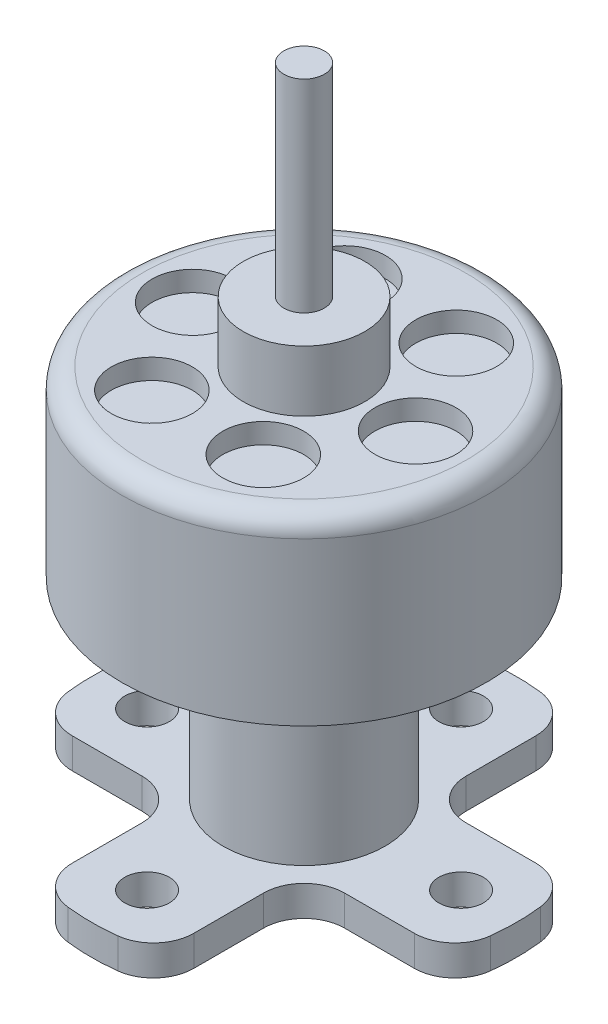
SolidWorks part; units mm, degrees
material "Liga 1060"
ref_plane "Plano frontal" through (0, 0, 0) normal (0, 0, 1) x (1, 0, 0)
ref_plane "Plano superior" through (0, 0, 0) normal (0, 1, 0) x (1, 0, 0)
ref_plane "Plano direito" through (0, 0, 0) normal (1, 0, 0) x (0, 0, -1)
sketch "Esboço1" plane through (0, 0, 0) normal (0, 1, 0) x (1, 0, 0)
  line L0 (-3, 3) -> (-3, 10.0623)
  line L1 (-10.0623, 3) -> (-3, 3)
  line L2 (3, 3) -> (3, 10.0623)
  line L3 (-10.0623, -3) -> (-3, -3)
  line L4 (3, -3) -> (10.0623, -3)
  line L5 (3, 3) -> (10.0623, 3)
  line L8 (3, -10.0623) -> (3, -3)
  line L10 (-3, -10.0623) -> (-3, -3)
  arc A0 (10.0623, -3) -> (10.0623, 3) centre (0, 0) ccw
  arc A1 (-3, -10.0623) -> (3, -10.0623) centre (0, 0) ccw
  arc A2 (-10.0623, 3) -> (-10.0623, -3) centre (0, 0) ccw
  arc A3 (3, 10.0623) -> (-3, 10.0623) centre (0, 0) ccw
  point P0 (0, 0)
  point P6 (0, 0)
  dimension "D2" = 10.5
  dimension "D1" = 6
extrude "Ressalto-extrusão1" add sketch "Esboço1" along normal blind 1.5
sketch "Esboço2" plane through (0, 1.5, 0) normal (0, 1, 0) x (1, 0, 0)
  line L0 (3, 3) -> (3, 10.0623) construction
  circle A0 centre (-7.75, 0) radius 1.1
  circle A1 centre (0, 7.75) radius 1.1
  circle A2 centre (7.75, 0) radius 1.1
  circle A3 centre (0, -7.75) radius 1.1
  point P12 (0, 0)
  dimension "D1" = 2.2
  dimension "D2" = 7.75
  dimension "D4" = 4.75
  dimension "D5" = 3
  dimension "D3" = 4
extrude "Corte-extrusão1" cut sketch "Esboço2" against normal up to next
fillet "Filete1" radius 2 12 edges at (10.0623, 0.75, 3) (3, 0.75, 3) (3, 0.75, 10.0623) (-3, 0.75, 10.0623) (-3, 0.75, 3) (-10.0623, 0.75, 3) (-10.0623, 0.75, -3) (-3, 0.75, -3) (-3, 0.75, -10.0623) (3, 0.75, -10.0623) (10.0623, 0.75, -3) (3, 0.75, -3)
sketch "Esboço3" plane through (0, 1.5, 0) normal (0, 1, 0) x (1, 0, 0)
  circle A0 centre (0, 0) radius 4
  dimension "D1" = 8
extrude "Ressalto-extrusão2" add sketch "Esboço3" along normal blind 9.5
sketch "Esboço4" plane through (0, 11, 0) normal (0, 1, 0) x (1, 0, 0)
  circle A0 centre (0, 0) radius 9
  dimension "D1" = 18
extrude "Ressalto-extrusão3" add sketch "Esboço4" along normal blind 9
fillet "Filete2" radius 1 1 edges at (0, 20, 9)
sketch "Esboço5" plane through (0, 20, 0) normal (0, 1, 0) x (1, 0, 0)
  circle A0 centre (0, 0) radius 3
  dimension "D1" = 6
extrude "Ressalto-extrusão4" add sketch "Esboço5" along normal blind 3
sketch "Esboço6" plane through (0, 23, 0) normal (0, 1, 0) x (1, 0, 0)
  circle A0 centre (0, 0) radius 1
  dimension "D1" = 2
extrude "Ressalto-extrusão5" add sketch "Esboço6" along normal blind 10
sketch "Esboço7" plane through (0, 20, 0) normal (0, 1, 0) x (1, 0, 0)
  circle A0 centre (-5.5, 0) radius 2
  circle A1 centre (-2.75, 4.7631) radius 2
  circle A2 centre (2.75, 4.7631) radius 2
  circle A3 centre (5.5, 0) radius 2
  circle A4 centre (2.75, -4.7631) radius 2
  circle A5 centre (-2.75, -4.7631) radius 2
  circle A6 centre (0, 0) radius 8 construction
  point P15 (0, 0)
  dimension "D1" = 4
  dimension "D2" = 5.5
  dimension "D4" = 2.75
  dimension "D5" = 5.5
  dimension "D3" = 6
extrude "Corte-extrusão2" cut sketch "Esboço7" against normal blind 1
